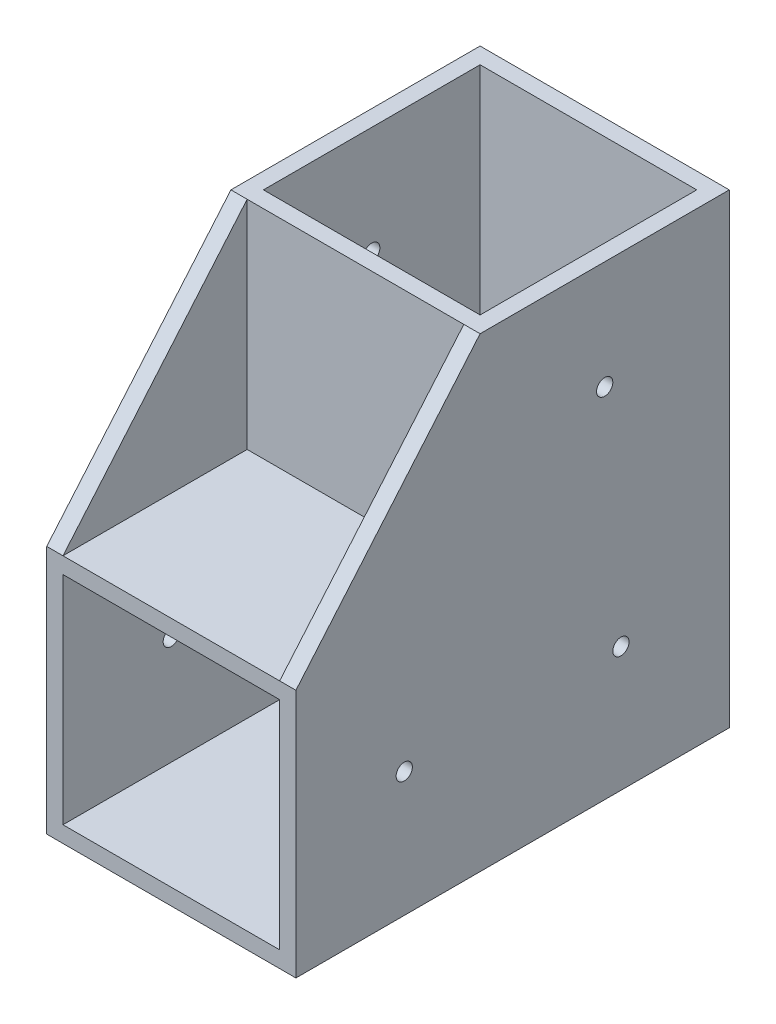
SolidWorks part; units mm, degrees
material "PA Type 6"
ref_plane "Front Plane" through (0, 0, 0) normal (0, 0, 1) x (1, 0, 0)
ref_plane "Top Plane" through (0, 0, 0) normal (0, 1, 0) x (1, 0, 0)
ref_plane "Right Plane" through (0, 0, 0) normal (1, 0, 0) x (0, 0, -1)
sketch "Esquisse1" plane through (0, 0, 0) normal (0, 0, 1) x (1, 0, 0)
  line L1 (0, 0) -> (46, 0)
  line L2 (0, 0) -> (0, -46)
  line L3 (0, -46) -> (46, -46)
  line L4 (46, 0) -> (46, -46)
  line L5 (3, -3) -> (43, -3)
  line L6 (3, -3) -> (3, -43)
  line L7 (3, -43) -> (43, -43)
  line L8 (43, -3) -> (43, -43)
  dimension "D1" = 40
  dimension "D2" = 3
  dimension "D3" = 3
  dimension "D4" = 3
extrude "Boss.-Extru.1" add sketch "Esquisse1" along normal blind 80
sketch "Esquisse2" plane through (0, 0, 0) normal (0, 1, 0) x (1, 0, 0)
  line L0 (46, -80) -> (46, 0) construction
  line L1 (0, 0) -> (46, 0)
  line L2 (0, 0) -> (0, -46)
  line L3 (0, -46) -> (46, -46)
  line L4 (46, 0) -> (46, -46)
  line L5 (3, -80) -> (3, 0) construction
  line L6 (3, -3) -> (43, -3)
  line L7 (3, -3) -> (3, -43)
  line L8 (3, -43) -> (43, -43)
  line L9 (43, -3) -> (43, -43)
  point P11 (3.4978, -43.4494)
  dimension "D1" = 40
  dimension "D2" = 3
extrude "Boss.-Extru.2" add sketch "Esquisse2" along normal blind 40
sketch "Esquisse3" plane through (46, 0, 0) normal (1, 0, 0) x (0, 0, -1)
  line L0 (-80, 0) -> (-46, 40)
  line L1 (-46, 40) -> (-46, 0)
  line L2 (-46, 0) -> (-80, 0)
extrude "Boss.-Extru.3" add sketch "Esquisse3" against normal blind 3
sketch "Esquisse4" plane through (0, 0, 0) normal (-1, 0, 0) x (0, 0, 1)
  line L0 (46, 40) -> (80, 0)
  line L1 (0, 40) -> (46, 40) construction
  line L2 (46, 0) -> (46, 40) construction
  line L3 (80, 0) -> (46, 0)
  line L4 (80, 0) -> (46, 0) construction
  line L5 (80, 0) -> (46, 0) construction
  line L6 (46, 0) -> (46, 40)
extrude "Boss.-Extru.4" add sketch "Esquisse4" against normal blind 3
sketch "Esquisse5" plane through (0, 0, 0) normal (-1, 0, 0) x (0, 0, 1)
  line L0 (20, -23) -> (60, -23) construction
  line L1 (40, -23) -> (40, -46) construction
  line L2 (80, -46) -> (0, -46) construction
  line L3 (3, 40) -> (43, 0) construction
  circle A0 centre (23, 20) radius 1.5
  circle A1 centre (20, -23) radius 1.5
  circle A2 centre (60, -23) radius 1.5
  point P10 (0, 0)
  point P14 (0, 0)
  point P15 (0, 0)
  dimension "D1" = 3
  dimension "D2" = 23
  dimension "D3" = 40
extrude "Enlèv. mat.-Extru.1" cut sketch "Esquisse5" against normal through all
